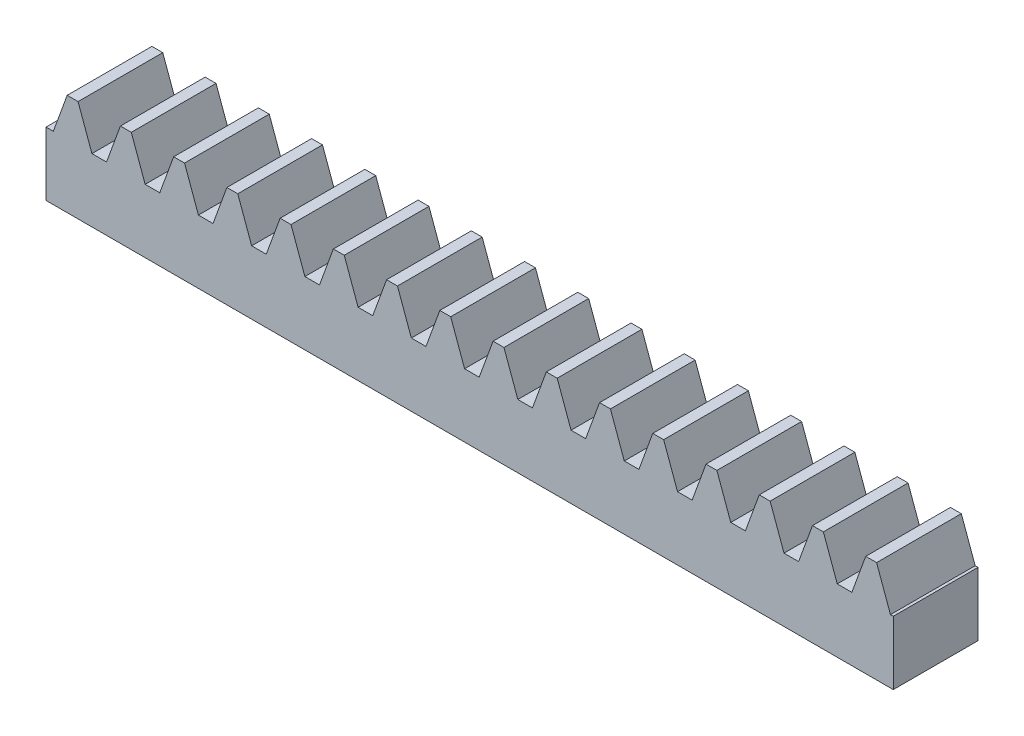
SolidWorks part; units mm, degrees
extrude "Blank" add sketch "BlankSke" against normal blind 10
sketch "BlankSke" plane through (0, 0, 0) normal (0, 0, 1) x (1, 0, 0)
  line L1 (0, 0) -> (100, 0)
  line L2 (0, 0) -> (0, 12)
  line L3 (0, 12) -> (100, 12)
  line L4 (100, 0) -> (100, 12)
  dimension "Length" = 100
  dimension "Blank_height" = 12
ref_plane "Plane1" through (0, 0, 0) normal (0, 0, 1) x (1, 0, 0)
ref_plane "Plane2" through (0, 0, 0) normal (0, 1, 0) x (1, 0, 0)
ref_plane "Plane3" through (0, 0, 0) normal (1, 0, 0) x (0, 0, -1)
sketch "HoldingSke" plane through (0, 0, 0) normal (0, 1, 0) x (1, 0, 0)
  line L0 (0, 0) -> (0.0696, 0.4951)
  line L1 (-15, 0) -> (100, 0) construction
  line L2 (0, 0) -> (-2.1039, 2.3779)
  line L3 (0, 0) -> (-11.863, 4.5341)
  line L4 (0, 0) -> (8.2587, 2.5249)
  line L5 (0, 0) -> (-23.7986, -8.8762)
  line L6 (0, 0) -> (-10.5278, -7.1032)
  line L9 (-71.009, 38.7566) -> (22.9603, 72.9586)
  line L10 (-76.2, 4.3779) -> (-66.2, 4.3779)
  line L11 (0, 0) -> (-10, 0)
  line L12 (-76.2, 101.6) -> (-76.133, 101.6)
  line L13 (24.9733, 27.94) -> (52.9518, 28.4284)
  line L14 (24.9733, 27.94) -> (24.9743, 27.94)
  line L15 (24.9733, 27.94) -> (100.4006, 29.5858)
  circle A0 centre (0, 0) radius 19.05
  circle A1 centre (0, 0) radius 5
  circle A2 centre (0, 0) radius 12.7
  dimension "MPH" = 10
  dimension "Diameter" = 38.1
  dimension "Num_teeth" = 17
  dimension "Pitch" = 0.5
  dimension "Show_teeth" = 998
  dimension "Thickness" = 12.7
  dimension "Ap" = 20
  dimension "Pitch_height" = 10
  dimension "Width" = 10
  dimension "Backlash" = 0.067
  dimension "Addendum_fac" = 1
  dimension "Dedendum_fac" = 1.25
  dimension "Clearance_fac" = 0.25
  dimension "Dedendum_add" = 0.001
  dimension "Length" = 100
  dimension "Module" = 2
sketch "TooCutSkeIll" plane through (0, 0, 0) normal (0, 0, 1) x (1, 0, 0)
  line L0 (-2.4806, 11.9474) -> (-0.9819, 7.8296)
  line L1 (-0.5111, 7.5) -> (0.5111, 7.5)
  line L2 (0.9819, 7.8296) -> (2.4806, 11.9474)
  line L3 (100, 12) -> (0, 12) construction
  line L4 (0, 0) -> (0, 64.897) construction
  line L5 (-13.208, 10) -> (12.954, 10) construction
  line L6 (0, 0) -> (100, 0) construction
  line L7 (1.7718, 10) -> (1.7718, 48.7463) construction
  line L8 (-1.7718, 10) -> (-1.7718, 48.7463) construction
  line L9 (2.5558, 12) -> (2.5558, 12.0254)
  line L10 (-2.5558, 12) -> (-2.5558, 12.0254)
  line L11 (-2.5558, 12.0254) -> (2.5558, 12.0254)
  arc A0 (0.5111, 7.5) -> (0.9819, 7.8296) centre (0.5111, 8.001) ccw
  arc A1 (-0.9819, 7.8296) -> (-0.5111, 7.5) centre (-0.5111, 8.001) ccw
  arc A2 (2.5558, 12) -> (2.4806, 11.9474) centre (2.5558, 11.92) ccw
  arc A3 (-2.4806, 11.9474) -> (-2.5558, 12) centre (-2.5558, 11.92) ccw
  dimension "Pitch_height" = 10
  dimension "Addendum_plus" = 2.0254
  dimension "Pressure_angle" = 20
  dimension "Gap_width" = 3.5436
  dimension "Dedendum" = 2.5
extrude "ToothCutIll" [suppressed] cut sketch "TooCutSkeIll" against normal through all
sketch "TooCutSkeSim" plane through (0, 0, 0) normal (0, 0, 1) x (1, 0, 0)
  line L0 (0.8619, 7.5) -> (-0.8619, 7.5)
  line L1 (2.509, 12.0254) -> (0.8619, 7.5)
  line L2 (0, 17.4625) -> (0, 53.467) construction
  line L3 (2.509, 12.0254) -> (-2.509, 12.0254)
  line L6 (-2.509, 12.0254) -> (-0.8619, 7.5)
  line L9 (-1.7718, 10) -> (1.7718, 10) construction
  line L10 (0, 0) -> (100, 0) construction
  line L11 (1.7718, 10) -> (1.7718, 53.467) construction
  line L12 (-1.7718, 10) -> (-1.7718, 53.467) construction
  dimension "Pitch_height" = 10
  dimension "Addendum_plus" = 2.0254
  dimension "Pressure_angle" = 20
  dimension "Gap_width" = 3.5436
  dimension "Dedendum" = 2.5
extrude "ToothCutSim" cut sketch "TooCutSkeSim" against normal through all
pattern_linear "TeethCuts" count 17 spacing 6.2832 along (1, 0, 0) of "ToothCutIll", "ToothCutSim"
equation "' \"Module@HoldingSke\" = 6.35"
equation "' \"Num_teeth@HoldingSke\" = 12"
equation "' \"Ap@HoldingSke\" =  20"
equation "' \"Ap@HoldingSke\" = 20"
equation "' \"Width@HoldingSke\" = 0.25 * 25.4"
equation "' \"Show_teeth@HoldingSke\" = 500"
equation "' \"Backlash@HoldingSke\" = 0.009 * 25.4"
equation "' \"Addendum_fac@HoldingSke\" = 1.0"
equation "' \"Dedendum_fac@HoldingSke\" = 1.25"
equation "' \"Dedendum_add@HoldingSke\" = 0.00005 * 25.4"
equation "' \"Clearance_fac@HoldingSke\" = 0.25"
equation "' \"Pitch_height@HoldingSke\" = 1 * 25.4"
equation "' \"Length@HoldingSke\" = 4.71 * 25.4"
equation "\"Pitch@HoldingSke\" = 1 / \"Module@HoldingSke\""
equation "\"MPH@HoldingSke\" = \"Dedendum_fac@HoldingSke\" / \"Pitch@HoldingSke\" + 2 * \"Dedendum_add@HoldingSke\" + 0.002 * 25.4"
equation "\"MPH@HoldingSke\" = ((sgn( \"MPH@HoldingSke\" - \"Pitch_height@HoldingSke\")+1)*( \"MPH@HoldingSke\" - \"Pitch_height@HoldingSke\"))/2 + \"Pitch_height@HoldingSke\""
equation "\"Blank_height@BlankSke\" = \"Pitch_height@HoldingSke\" + \"Addendum_fac@HoldingSke\"  / \"Pitch@HoldingSke\" "
equation "\"Length@BlankSke\" =  \"Length@HoldingSke\""
equation "\"Face_width@Blank\" = \"Width@HoldingSke\""
equation "\"Pressure_angle@TooCutSkeIll\" = \"Ap@HoldingSke\""
equation "\"Addendum_plus@TooCutSkeIll\" =  \"Addendum_fac@HoldingSke\"  / \"Pitch@HoldingSke\" + 0.001 *25.4"
equation "\"Dedendum@TooCutSkeIll\" = \"Dedendum_fac@HoldingSke\"  / \"Pitch@HoldingSke\""
equation "\"Pitch_height@TooCutSkeIll\" =  \"MPH@HoldingSke\""
equation "\"Gap_width@TooCutSkeIll\" = 3.14159265 / 2 / \"Pitch@HoldingSke\" + 6 * \"Backlash@HoldingSke\""
equation "\"Pressure_angle@TooCutSkeSim\" = \"Ap@HoldingSke\""
equation "\"Addendum_plus@TooCutSkeSim\" =  \"Addendum_fac@HoldingSke\"  / \"Pitch@HoldingSke\" + 0.001 * 25.4"
equation "\"Dedendum@TooCutSkeSim\" = \"Dedendum_fac@HoldingSke\"  / \"Pitch@HoldingSke\""
equation "\"Pitch_height@TooCutSkeSim\" =  \"MPH@HoldingSke\""
equation "\"Gap_width@TooCutSkeSim\" = 3.14159265 / 2 / \"Pitch@HoldingSke\" + 6 * \"Backlash@HoldingSke\""
equation "\"Root_fillet@TooCutSkeIll\" = \"Clearance_fac@HoldingSke\" / \"Pitch@HoldingSke\" + \"Dedendum_add@HoldingSke\""
equation "\"Break_rad@TooCutSkeIll\" = 0.02 / \"Pitch@HoldingSke\" * 2"
equation "\"Linear_pitch@TeethCuts\" = 3.14159265 / \"Pitch@HoldingSke\""
equation "\"Num_teeth@HoldingSke\" = int( ( \"Length@HoldingSke\" + 0 ) / (3.14159265 / \"Pitch@HoldingSke\")) + 0.9999  + 1"
equation " \"Num_teeth@TeethCuts\" = int( \"Show_teeth@HoldingSke\" ) + 1"
equation " \"Num_teeth@TeethCuts\" = ((sgn( \"Num_teeth@TeethCuts\" - \"Num_teeth@HoldingSke\" )-1)*( \"Num_teeth@TeethCuts\" - \"Num_teeth@HoldingSke\" ))/-2+ \"Num_teeth@HoldingSke\""
equation " \"Num_teeth@TeethCuts\" = ((sgn( \"Num_teeth@TeethCuts\" - 2.0)+1)*( \"Num_teeth@TeethCuts\" - 2.0))/2 +2.0"
